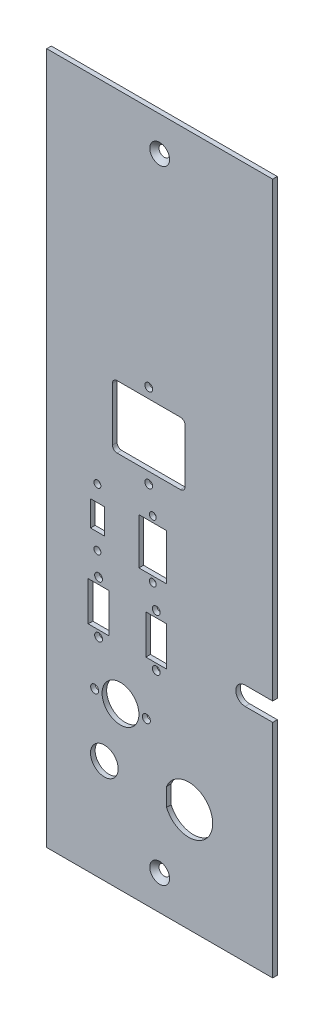
SolidWorks part; units mm, degrees
ref_plane "Ebene vorne" through (0, 0, 0) normal (0, 0, 1) x (1, 0, 0)
ref_plane "Ebene oben" through (0, 0, 0) normal (0, 1, 0) x (1, 0, 0)
ref_plane "Ebene rechts" through (0, 0, 0) normal (1, 0, 0) x (0, 0, -1)
sketch "Skizze2" plane through (0, 0, 0) normal (0, 0, 1) x (1, 0, 0)
  line L0 (-3, 94.7115) -> (95, 94.7115)
  line L1 (95, 94.7115) -> (95, -205.2885)
  line L2 (95, -205.2885) -> (-3, -205.2885)
  line L3 (-3, -205.2885) -> (-3, 94.7115)
  dimension "D1" = 98
  dimension "D2" = 300
  dimension "D3" = 98
  dimension "D4" = 90
extrude "Aufsatz-Linear austragen1" add sketch "Skizze2" along normal blind 2
hole_wizard "Formsenkung für M4 Senkschraube mit Innensechskant1" positions "Skizze3" profile "Skizze4" countersink size "M4" standard "DIN" end condition through all
sketch "Skizze3" plane through (0, 0, 2) normal (0, 0, 1) x (1, 0, 0)
  line L0 (46, 94.7115) -> (46, -205.2885) construction
  line L1 (95, 94.7115) -> (-3, 94.7115) construction
  line L2 (-3, -205.2885) -> (95, -205.2885) construction
  point P11 (46, -190.2885)
  point P13 (46, 79.7115)
  dimension "D1" = 15
  dimension "D2" = 15
sketch "Skizze4" plane through (46, 79.7115, 2) normal (1, 0, 0) x (0, -1, 0)
  line L0 (0, 0) -> (0, 2)
  line L1 (0, 2) -> (2.25, 2)
  line L2 (2.25, 2) -> (2.25, 2.05)
  line L3 (2.25, 2.05) -> (4.3, 0)
  line L5 (4.3, 0) -> (0, 0)
  line L6 (-2.25, 2.05) -> (-4.3, 0) construction
  line L11 (0, -6.35) -> (0, 107.95) construction
  dimension "Bohrerdurchmesser" = 4.5
  dimension "Bohrungstiefe" = 2
  dimension "Senkdurchmesser (Oben)" = 8.6
  dimension "Senkwinkel (Oben)" = 90
sketch "Skizze6" plane through (0, 0, 2) normal (0, 0, 1) x (1, 0, 0)
  line L1 (27.5, -14.6885) -> (55, -14.6885)
  line L2 (25.5, -16.6885) -> (25.5, -39.8885)
  line L3 (27.5, -41.8885) -> (55, -41.8885)
  line L4 (57, -16.6885) -> (57, -39.8885)
  line L16 (-3, 94.7115) -> (-3, -205.2885) construction
  line L17 (95, -205.2885) -> (95, 94.7115) construction
  line L19 (40, -95.2885) -> (49, -95.2885)
  line L20 (40, -95.2885) -> (40, -112.2885)
  line L21 (40, -112.2885) -> (49, -112.2885)
  line L22 (49, -95.2885) -> (49, -112.2885)
  line L23 (58.6, -160.2885) -> (43.3779, -160.2885) construction
  line L24 (-3, -205.2885) -> (95, -205.2885) construction
  line L25 (49, -70.2885) -> (-30.7092, -70.2885) construction
  line L26 (49, -80.2885) -> (37, -80.2885)
  line L27 (49, -80.2885) -> (49, -60.2885)
  line L28 (49, -60.2885) -> (37, -60.2885)
  line L29 (37, -80.2885) -> (37, -60.2885)
  line L30 (16, -64.7885) -> (22, -64.7885)
  line L31 (16, -64.7885) -> (16, -75.7885)
  line L32 (16, -75.7885) -> (22, -75.7885)
  line L33 (22, -64.7885) -> (22, -75.7885)
  line L34 (49, -164.223) -> (49, -156.3539)
  line L35 (68.2, -164.223) -> (49, -156.3539) construction
  line L36 (68.0098, -156.4319) -> (49, -164.223) construction
  line L40 (95, 94.7115) -> (-3, 94.7115) construction
  line L41 (15, -112.2885) -> (24, -112.2885)
  line L42 (24, -95.2885) -> (24, -112.2885)
  line L43 (15, -95.2885) -> (15, -112.2885)
  line L44 (15, -95.2885) -> (24, -95.2885)
  line L45 (95, -101.2885) -> (83, -101.2885)
  line L46 (95, -101.2885) -> (95, -109.2885)
  line L47 (95, -109.2885) -> (83, -109.2885)
  arc A0 (25.5, -39.8885) -> (27.5, -41.8885) centre (27.5, -39.8885) ccw
  arc A1 (57, -39.8885) -> (55, -41.8885) centre (55, -39.8885) cw
  arc A2 (55, -14.6885) -> (57, -16.6885) centre (55, -16.6885) cw
  arc A3 (27.5, -14.6885) -> (25.5, -16.6885) centre (27.5, -16.6885) ccw
  circle A4 centre (41.25, -10.2885) radius 1.7
  circle A5 centre (41.25, -46.6885) radius 1.7
  circle A6 centre (44.5, -92.5385) radius 1.7
  circle A7 centre (44.5, -115.0385) radius 1.7
  circle A8 centre (29, -135.2885) radius 8
  circle A11 centre (43, -57.7885) radius 1.5
  circle A12 centre (43, -82.7885) radius 1.5
  arc A13 (49, -164.223) -> (49, -156.3539) centre (58.6, -160.2885) ccw
  circle A14 centre (22, -160.2885) radius 6
  circle A17 centre (40.2, -135.2885) radius 1.75
  circle A18 centre (17.8, -135.2885) radius 1.75
  circle A19 centre (19.5, -115.0385) radius 1.7
  circle A20 centre (19.5, -92.5385) radius 1.7
  arc A21 (83, -101.2885) -> (83, -109.2885) centre (83, -105.2885) ccw
  circle A22 centre (19, -57.7885) radius 1.5
  circle A23 centre (19, -82.7885) radius 1.5
  dimension "D3" = 3.4
  dimension "D4" = 3.4
  dimension "D7" = 15.75
  dimension "D8" = 15.75
  dimension "D9" = 2
  dimension "D10" = 60
  dimension "D14" = 3.4
  dimension "D15" = 3.4
  dimension "D19" = 16
  dimension "D20" = 3.5
  dimension "D21" = 3.5
  dimension "D29" = 3
  dimension "D30" = 3
  dimension "D36" = 10.375
  dimension "D38" = 12
  dimension "D11" = 105
  dimension "D23" = 52
  dimension "D39" = 0
  dimension "D42" = 230
  dimension "D43" = 32
  dimension "D44" = 45
  dimension "D22" = 11.2
  dimension "D24" = 11.2
  dimension "D47" = 25
  dimension "D51" = 16
  dimension "D54" = 4
  dimension "D56" = 20.5
  dimension "D57" = 20.5
  dimension "D60" = 3.4
  dimension "D61" = 3.4
  dimension "D62" = 22.5
  dimension "D66" = 3
  dimension "D67" = 3
  dimension "D68" = 25
  dimension "D72" = 6
  dimension "D1" = 23.2
  dimension "D2" = 27.5
  dimension "D5" = 36.4
  dimension "D6" = 4.4
  dimension "D12" = 9
  dimension "D13" = 17
  dimension "D16" = 22.5
  dimension "D17" = 2.75
  dimension "D18" = 4.5
  dimension "D25" = 20
  dimension "D26" = 12
  dimension "D27" = 25
  dimension "D28" = 2.5
  dimension "D31" = 11
  dimension "D32" = 6
  dimension "D33" = 5.5
  dimension "D34" = 6
  dimension "D35" = 19.2
  dimension "D37" = 7.8691
  dimension "D40" = 165
  dimension "D41" = 15
  dimension "D45" = 0
  dimension "D46" = 4.5
  dimension "D48" = 52
  dimension "D49" = 52
  dimension "D50" = 45
  dimension "D52" = 96
  dimension "D53" = 8
  dimension "D55" = 12
  dimension "D58" = 17
  dimension "D59" = 9
  dimension "D63" = 2.75
  dimension "D64" = 110
  dimension "D65" = 93
  dimension "D69" = 7
  dimension "D70" = 3
  dimension "D71" = 3
extrude "Schnitt-Linear austragen1" cut sketch "Skizze6" against normal blind 10
